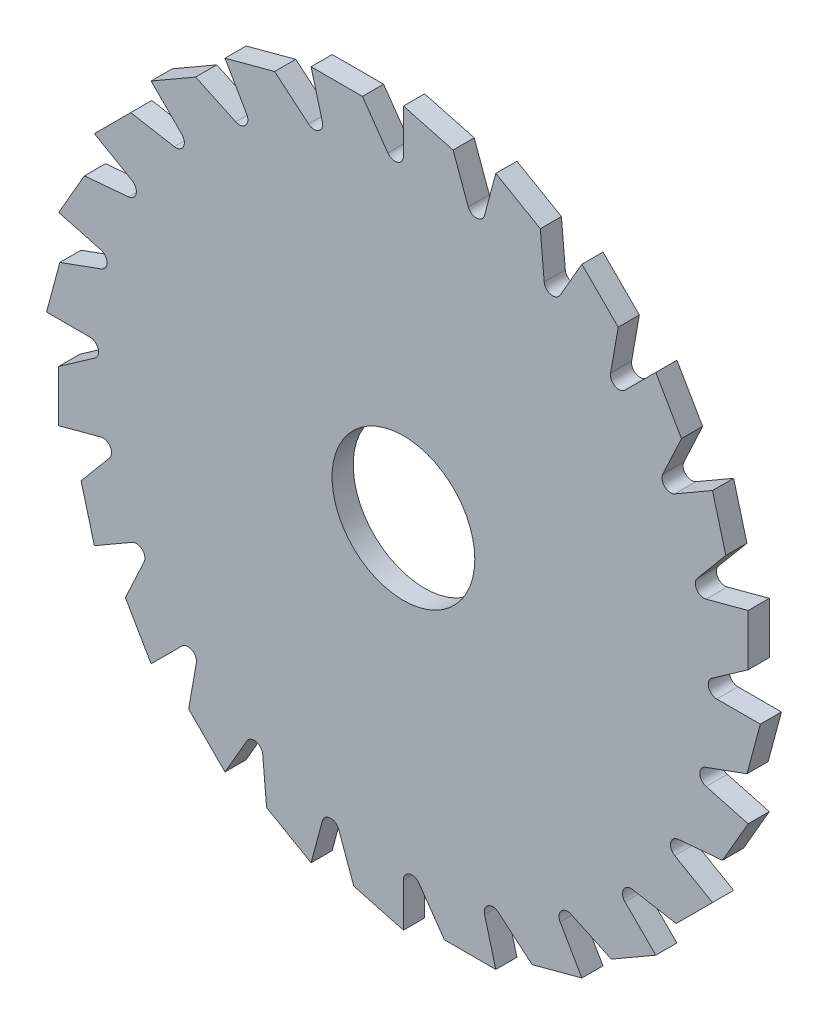
SolidWorks part; units mm, degrees
ref_plane "Front Plane" through (0, 0, 0) normal (0, 0, 1) x (1, 0, 0)
ref_plane "Top Plane" through (0, 0, 0) normal (0, 1, 0) x (1, 0, 0)
ref_plane "Right Plane" through (0, 0, 0) normal (1, 0, 0) x (0, 0, -1)
sketch "Sketch1" plane through (0, 0, 0) normal (0, 0, 1) x (1, 0, 0)
  line L0 (0, 31.75) -> (4.4162, 30.5667)
  line L1 (4.4162, 30.5667) -> (5.7634, 26.8652)
  line L2 (7.2155, 26.9286) -> (8.2175, 30.6681)
  line L3 (0, 31.75) -> (0, 0) construction
  line L4 (0, 0) -> (8.2175, 30.6681) construction
  line L5 (0, 31.75) -> (12.0811, 31.75) construction
  line L6 (6.3024, 26.3847) -> (0, 0) construction
  line L7 (6.3024, 26.3847) -> (4.0698, 26.918) construction
  line L8 (13.9393, 24.1436) -> (15.875, 27.4963)
  line L9 (12.177, 28.3821) -> (12.5203, 24.4581)
  line L10 (8.2175, 30.6681) -> (12.177, 28.3821)
  line L11 (19.7131, 19.7131) -> (22.4506, 22.4506)
  line L12 (19.1079, 24.2634) -> (18.4239, 20.3843)
  line L13 (15.875, 27.4963) -> (19.1079, 24.2634)
  line L14 (24.1436, 13.9393) -> (27.4963, 15.875)
  line L15 (24.7366, 18.4912) -> (23.072, 14.9212)
  line L16 (22.4506, 22.4506) -> (24.7366, 18.4912)
  line L17 (26.9286, 7.2155) -> (30.6681, 8.2175)
  line L18 (28.6796, 11.4588) -> (26.1477, 8.4413)
  line L19 (27.4963, 15.875) -> (28.6796, 11.4588)
  line L20 (27.8786, 0) -> (31.75, 0)
  line L21 (30.6681, 3.6455) -> (27.4415, 1.3862)
  line L22 (30.6681, 8.2175) -> (30.6681, 3.6455)
  line L23 (26.9286, -7.2155) -> (30.6681, -8.2175)
  line L24 (30.5667, -4.4162) -> (26.8652, -5.7634)
  line L25 (31.75, 0) -> (30.5667, -4.4162)
  line L26 (24.1436, -13.9393) -> (27.4963, -15.875)
  line L27 (28.3821, -12.177) -> (24.4581, -12.5203)
  line L28 (30.6681, -8.2175) -> (28.3821, -12.177)
  line L29 (19.7131, -19.7131) -> (22.4506, -22.4506)
  line L30 (24.2634, -19.1079) -> (20.3843, -18.4239)
  line L31 (27.4963, -15.875) -> (24.2634, -19.1079)
  line L32 (13.9393, -24.1436) -> (15.875, -27.4963)
  line L33 (18.4912, -24.7366) -> (14.9212, -23.072)
  line L34 (22.4506, -22.4506) -> (18.4912, -24.7366)
  line L35 (7.2155, -26.9286) -> (8.2175, -30.6681)
  line L36 (11.4588, -28.6796) -> (8.4413, -26.1477)
  line L37 (15.875, -27.4963) -> (11.4588, -28.6796)
  line L38 (0, -27.8786) -> (0, -31.75)
  line L39 (3.6455, -30.6681) -> (1.3862, -27.4415)
  line L40 (8.2175, -30.6681) -> (3.6455, -30.6681)
  line L41 (-7.2155, -26.9286) -> (-8.2175, -30.6681)
  line L42 (-4.4162, -30.5667) -> (-5.7634, -26.8652)
  line L43 (0, -31.75) -> (-4.4162, -30.5667)
  line L44 (-13.9393, -24.1436) -> (-15.875, -27.4963)
  line L45 (-12.177, -28.3821) -> (-12.5203, -24.4581)
  line L46 (-8.2175, -30.6681) -> (-12.177, -28.3821)
  line L47 (-19.7131, -19.7131) -> (-22.4506, -22.4506)
  line L48 (-19.1079, -24.2634) -> (-18.4239, -20.3843)
  line L49 (-15.875, -27.4963) -> (-19.1079, -24.2634)
  line L50 (-24.1436, -13.9393) -> (-27.4963, -15.875)
  line L51 (-24.7366, -18.4912) -> (-23.072, -14.9212)
  line L52 (-22.4506, -22.4506) -> (-24.7366, -18.4912)
  line L53 (-26.9286, -7.2155) -> (-30.6681, -8.2175)
  line L54 (-28.6796, -11.4588) -> (-26.1477, -8.4413)
  line L55 (-27.4963, -15.875) -> (-28.6796, -11.4588)
  line L56 (-27.8786, 0) -> (-31.75, 0)
  line L57 (-30.6681, -3.6455) -> (-27.4415, -1.3862)
  line L58 (-30.6681, -8.2175) -> (-30.6681, -3.6455)
  line L59 (-26.9286, 7.2155) -> (-30.6681, 8.2175)
  line L60 (-30.5667, 4.4162) -> (-26.8652, 5.7634)
  line L61 (-31.75, 0) -> (-30.5667, 4.4162)
  line L62 (-24.1436, 13.9393) -> (-27.4963, 15.875)
  line L63 (-28.3821, 12.177) -> (-24.4581, 12.5203)
  line L64 (-30.6681, 8.2175) -> (-28.3821, 12.177)
  line L65 (-19.7131, 19.7131) -> (-22.4506, 22.4506)
  line L66 (-24.2634, 19.1079) -> (-20.3843, 18.4239)
  line L67 (-27.4963, 15.875) -> (-24.2634, 19.1079)
  line L68 (-13.9393, 24.1436) -> (-15.875, 27.4963)
  line L69 (-18.4912, 24.7366) -> (-14.9212, 23.072)
  line L70 (-22.4506, 22.4506) -> (-18.4912, 24.7366)
  line L71 (-7.2155, 26.9286) -> (-8.2175, 30.6681)
  line L72 (-11.4588, 28.6796) -> (-8.4413, 26.1477)
  line L73 (-15.875, 27.4963) -> (-11.4588, 28.6796)
  line L74 (0, 27.8786) -> (0, 31.75)
  line L75 (-3.6455, 30.6681) -> (-1.3862, 27.4415)
  line L76 (-8.2175, 30.6681) -> (-3.6455, 30.6681)
  circle A0 centre (0, 0) radius 31.75 construction
  circle A1 centre (0, 0) radius 6.35
  circle A2 centre (0, 0) radius 27.127 construction
  arc A3 (5.7634, 26.8652) -> (7.2155, 26.9286) centre (6.4795, 27.1259) ccw
  arc A4 (12.5203, 24.4581) -> (13.9393, 24.1436) centre (13.2794, 24.5246) ccw
  arc A5 (18.4239, 20.3843) -> (19.7131, 19.7131) centre (19.1743, 20.2519) ccw
  arc A6 (23.072, 14.9212) -> (24.1436, 13.9393) centre (23.7626, 14.5992) ccw
  arc A7 (26.1477, 8.4413) -> (26.9286, 7.2155) centre (26.7314, 7.9515) ccw
  arc A8 (27.4415, 1.3862) -> (27.8786, 0) centre (27.8786, 0.762) ccw
  arc A9 (26.8652, -5.7634) -> (26.9286, -7.2155) centre (27.1259, -6.4795) ccw
  arc A10 (24.4581, -12.5203) -> (24.1436, -13.9393) centre (24.5246, -13.2794) ccw
  arc A11 (20.3843, -18.4239) -> (19.7131, -19.7131) centre (20.2519, -19.1743) ccw
  arc A12 (14.9212, -23.072) -> (13.9393, -24.1436) centre (14.5992, -23.7626) ccw
  arc A13 (8.4413, -26.1477) -> (7.2155, -26.9286) centre (7.9515, -26.7314) ccw
  arc A14 (1.3862, -27.4415) -> (0, -27.8786) centre (0.762, -27.8786) ccw
  arc A15 (-5.7634, -26.8652) -> (-7.2155, -26.9286) centre (-6.4795, -27.1259) ccw
  arc A16 (-12.5203, -24.4581) -> (-13.9393, -24.1436) centre (-13.2794, -24.5246) ccw
  arc A17 (-18.4239, -20.3843) -> (-19.7131, -19.7131) centre (-19.1743, -20.2519) ccw
  arc A18 (-23.072, -14.9212) -> (-24.1436, -13.9393) centre (-23.7626, -14.5992) ccw
  arc A19 (-26.1477, -8.4413) -> (-26.9286, -7.2155) centre (-26.7314, -7.9515) ccw
  arc A20 (-27.4415, -1.3862) -> (-27.8786, 0) centre (-27.8786, -0.762) ccw
  arc A21 (-26.8652, 5.7634) -> (-26.9286, 7.2155) centre (-27.1259, 6.4795) ccw
  arc A22 (-24.4581, 12.5203) -> (-24.1436, 13.9393) centre (-24.5246, 13.2794) ccw
  arc A23 (-20.3843, 18.4239) -> (-19.7131, 19.7131) centre (-20.2519, 19.1743) ccw
  arc A24 (-14.9212, 23.072) -> (-13.9393, 24.1436) centre (-14.5992, 23.7626) ccw
  arc A25 (-8.4413, 26.1477) -> (-7.2155, 26.9286) centre (-7.9515, 26.7314) ccw
  arc A26 (-1.3862, 27.4415) -> (0, 27.8786) centre (-0.762, 27.8786) ccw
  dimension "D1" = 63.5
  dimension "D2" = 12.7
  dimension "D3" = 125
  dimension "D7" = 0.762
  dimension "D4" = 15
  dimension "D5" = 15
  dimension "D6" = 4.572
  dimension "D8" = 24
extrude "Boss-Extrude1" add sketch "Sketch1" along normal blind 1.8796 contours A26 L75 L76 L71 A25 L72 L73 L68 A24 L69 L70 L65 A23 L66 L67 L62 A22 L63 L64 L59 A21 L60 L61 L56 A20 L57 L58 L53 A19 L54 L55 L50 A18 L51 L52 L47 A17 L48 L49 L44 A16 L45 L46 L41 A15 L42 L43 L38 A14 L39 L40
